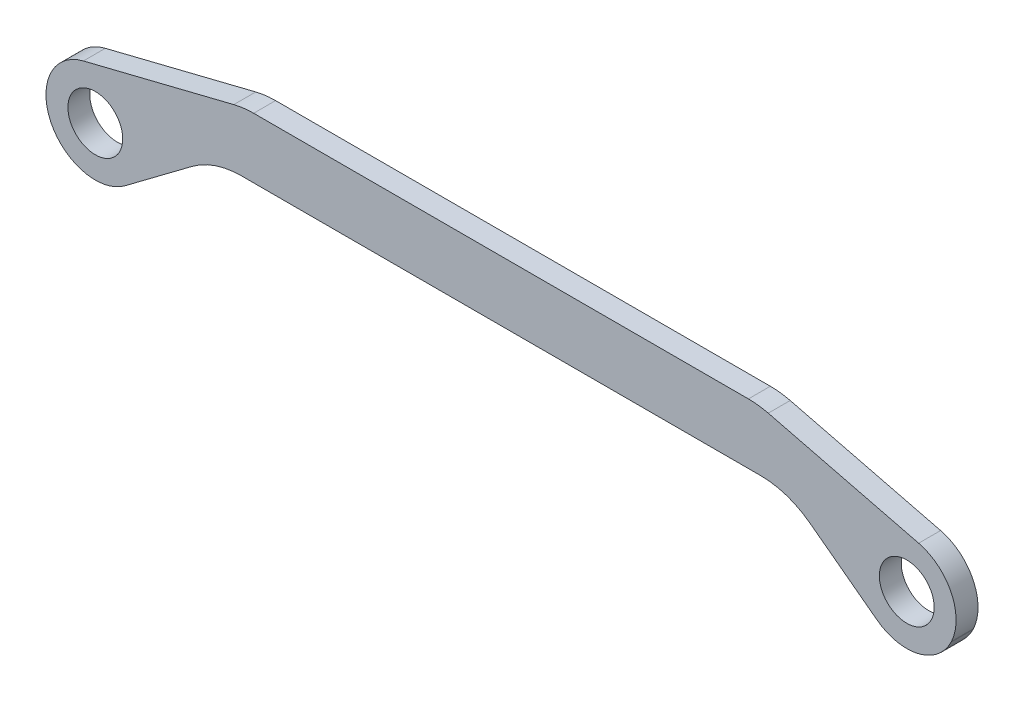
SolidWorks part; units mm, degrees
ref_plane "前视基准面" through (0, 0, 0) normal (0, 0, 1) x (1, 0, 0)
ref_plane "上视基准面" through (0, 0, 0) normal (0, 1, 0) x (1, 0, 0)
ref_plane "右视基准面" through (0, 0, 0) normal (1, 0, 0) x (0, 0, -1)
sketch "草图1" plane through (0, 0, 0) normal (0, 0, 1) x (1, 0, 0)
  line B0 (28.8804, 16) -> (119.1196, 16)
  line B1 (121.3326, 5) -> (26.6674, 5)
  line B2 (-2.1723, 8.7339) -> (25.2601, 15.5566)
  line B3 (122.7399, 15.5566) -> (150.1723, 8.7339)
  line B4 (17.6677, 2.0002) -> (5.4, -7.2)
  line B5 (156.1712, -3.7725) -> (156.0853, -3.9531)
  line B6 (142.6, -7.2) -> (130.3323, 2.0002)
  line B7 (-8.1712, -3.7725) -> (-8.0853, -3.9531)
  arc B8 (130.3323, 2.0002) -> (121.3326, 5) centre (121.3326, -10) ccw
  arc B9 (26.6674, 5) -> (17.6677, 2.0002) centre (26.6674, -10) ccw
  arc B10 (28.8804, 16) -> (25.2601, 15.5566) centre (28.8804, 1) ccw
  arc B11 (122.7399, 15.5566) -> (119.1196, 16) centre (119.1196, 1) ccw
  arc B12 (-8.0853, -3.9531) -> (5.4, -7.2) centre (0, 0) ccw
  arc B13 (-2.1723, 8.7339) -> (-8.1712, -3.7725) centre (0, 0) ccw
  arc B14 (156.1712, -3.7725) -> (150.1723, 8.7339) centre (148, 0) ccw
  arc B15 (142.6, -7.2) -> (156.0853, -3.9531) centre (148, 0) ccw
  circle B16 centre (0, 0) radius 4.4
  circle B17 centre (148, 0) radius 4.4
sketch_block_instance "C5_0-1"
sketch_block "C5_0"
extrude "凸台-拉伸1" add sketch "草图1" along normal blind 4
sketch "草图2" plane through (0, 0, 4) normal (0, 0, 1) x (1, 0, 0)
  circle A0 centre (0, 0) radius 5
  circle A1 centre (148, 0) radius 5
  dimension "D1" = 10
  dimension "D2" = 10
extrude "切除-拉伸1" cut sketch "草图2" against normal through all
